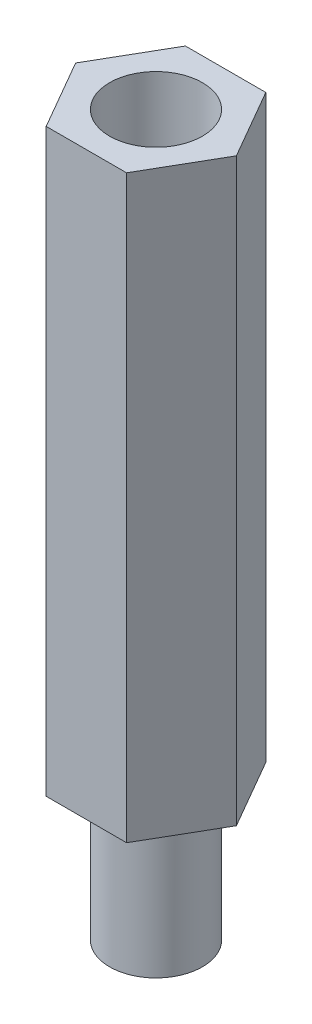
SolidWorks part; units mm, degrees
ref_plane "前视基准面" through (0, 0, 0) normal (0, 0, 1) x (1, 0, 0)
ref_plane "上视基准面" through (0, 0, 0) normal (0, 1, 0) x (1, 0, 0)
ref_plane "右视基准面" through (0, 0, 0) normal (1, 0, 0) x (0, 0, -1)
sketch "草图1" plane through (0, 0, 0) normal (0, 1, 0) x (1, 0, 0)
  line L1 (3.4641, 0) -> (1.7321, 3)
  line L2 (1.7321, 3) -> (-1.7321, 3)
  line L3 (-1.7321, 3) -> (-3.4641, 0)
  line L4 (-3.4641, 0) -> (-1.7321, -3)
  line L5 (-1.7321, -3) -> (1.7321, -3)
  line L6 (1.7321, -3) -> (3.4641, 0)
  circle A0 centre (0, 0) radius 3 construction
  circle A1 centre (0, 0) radius 2
  dimension "D1" = 6
  dimension "D2" = 4
extrude "凸台-拉伸1" add sketch "草图1" along normal blind 25
sketch "草图2" plane through (0, 0, 0) normal (0, -1, 0) x (1, 0, 0)
  circle A0 centre (0, 0) radius 2
extrude "凸台-拉伸2" add sketch "草图2" along normal blind 6 and the other way blind 5
